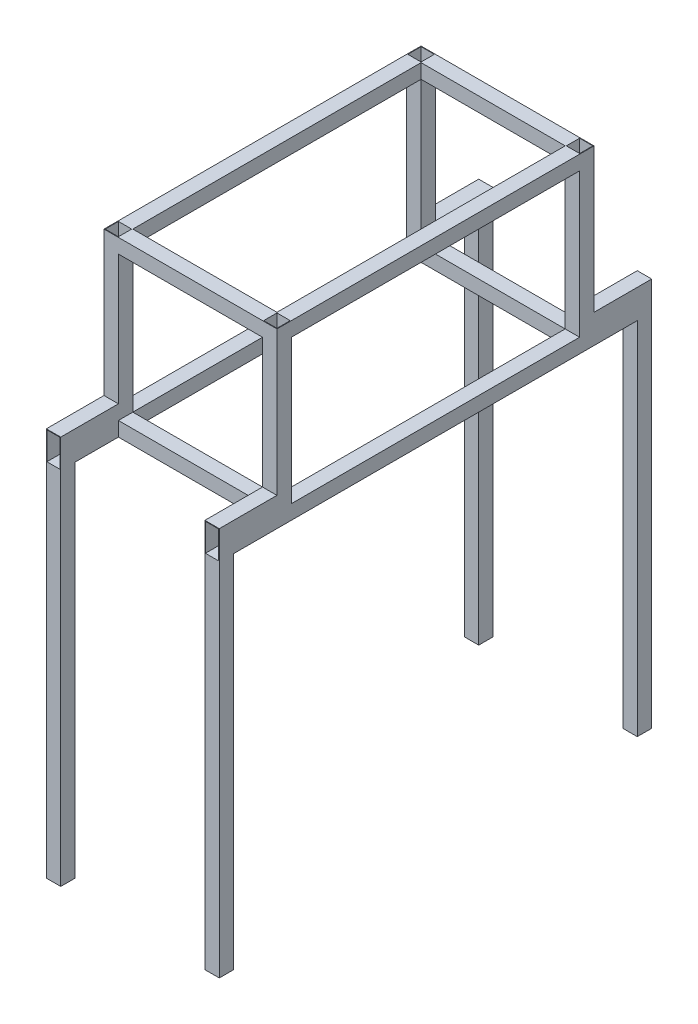
SolidWorks part; units mm, degrees
material "1023 Carbon Steel Sheet (SS)"
ref_plane "Front Plane" through (0, 0, 0) normal (0, 0, 1) x (1, 0, 0)
ref_plane "Top Plane" through (0, 0, 0) normal (0, 1, 0) x (1, 0, 0)
ref_plane "Right Plane" through (0, 0, 0) normal (1, 0, 0) x (0, 0, -1)
sketch "Sketch1" plane through (0, 0, 0) normal (0, 1, 0) x (1, 0, 0)
  line L0 (-128, 255) -> (-151.4, 255)
  line L1 (-127, 254) -> (127, 254) construction
  line L2 (-127, 254) -> (-127, -254) construction
  line L3 (-127, -254) -> (127, -254) construction
  line L4 (127, 254) -> (127, -254) construction
  line L5 (-127, 254) -> (127, -254) construction
  line L6 (-127, -254) -> (127, 254) construction
  line L7 (127, 254) -> (152.4, 254)
  line L8 (127, 254) -> (127, 279.4)
  line L9 (127, 279.4) -> (152.4, 279.4)
  line L10 (152.4, 254) -> (152.4, 279.4)
  line L11 (127, -254) -> (152.4, -254)
  line L12 (127, -254) -> (127, -279.4)
  line L13 (127, -279.4) -> (152.4, -279.4)
  line L14 (152.4, -254) -> (152.4, -279.4)
  line L15 (-127, -254) -> (-152.4, -254)
  line L16 (-127, -254) -> (-127, -279.4)
  line L17 (-127, -279.4) -> (-152.4, -279.4)
  line L18 (-152.4, -254) -> (-152.4, -279.4)
  line L19 (-127, 254) -> (-152.4, 254)
  line L20 (-127, 254) -> (-127, 279.4)
  line L21 (-127, 279.4) -> (-152.4, 279.4)
  line L22 (-152.4, 254) -> (-152.4, 279.4)
  line L23 (-151.4, 255) -> (-151.4, 278.4)
  line L24 (-128, 278.4) -> (-151.4, 278.4)
  line L25 (-128, 255) -> (-128, 278.4)
  line L26 (128, 255) -> (151.4, 255)
  line L27 (151.4, 255) -> (151.4, 278.4)
  line L28 (128, 278.4) -> (151.4, 278.4)
  line L29 (128, 255) -> (128, 278.4)
  line L30 (-128, -255) -> (-151.4, -255)
  line L31 (-151.4, -255) -> (-151.4, -278.4)
  line L32 (-128, -278.4) -> (-151.4, -278.4)
  line L33 (-128, -255) -> (-128, -278.4)
  line L34 (128, -255) -> (151.4, -255)
  line L35 (151.4, -255) -> (151.4, -278.4)
  line L36 (128, -278.4) -> (151.4, -278.4)
  line L37 (128, -255) -> (128, -278.4)
  point P0 (0, 0)
  dimension "D1" = 254
  dimension "D2" = 508
  dimension "D3" = 25.4
  dimension "D4" = 25.4
  dimension "D5" = 25.4
  dimension "D6" = 25.4
  dimension "D7" = 25.4
  dimension "D8" = 25.4
  dimension "D9" = 25.4
  dimension "D10" = 25.4
  dimension "D11" = 1
  dimension "D12" = 1
extrude "Boss-Extrude1" add sketch "Sketch1" along normal blind 304.8 contours L15 L18 L17 L16 | L11 L14 L13 L12 | L7 L10 L9 L8 | L19 L22 L21 L20 | L30 L31 L32 L33 | L34 L35 L36 L37 | L26 L27 L28 L29 | L0 L23 L24 L25
sketch "Sketch2" plane through (0, 0, -254) normal (0, 0, 1) x (1, 0, 0)
  line L0 (152.4, 304.8) -> (152.4, 0) construction
  line L1 (127, 304.8) -> (152.4, 304.8)
  line L2 (127, 304.8) -> (127, 279.4)
  line L3 (127, 279.4) -> (152.4, 279.4)
  line L4 (152.4, 304.8) -> (152.4, 279.4)
  line L5 (128, 280.4) -> (151.4, 280.4)
  line L6 (151.4, 303.8) -> (151.4, 280.4)
  line L7 (128, 303.8) -> (151.4, 303.8)
  line L8 (128, 303.8) -> (128, 280.4)
  line L9 (127, 25.4) -> (152.4, 25.4)
  line L10 (127, 25.4) -> (127, 0)
  line L11 (127, 0) -> (152.4, 0)
  line L12 (152.4, 25.4) -> (152.4, 0)
  line L13 (128, 1) -> (151.4, 1)
  line L14 (151.4, 24.4) -> (151.4, 1)
  line L15 (128, 24.4) -> (151.4, 24.4)
  line L16 (128, 24.4) -> (128, 1)
  line L17 (127, 0) -> (152.4, 0) construction
  dimension "D1" = 25.4
  dimension "D3" = 23.4
  dimension "D4" = 25.4
  dimension "D5" = 25.4
  dimension "D6" = 1
  dimension "D7" = 1
  dimension "D8" = 1
  dimension "D9" = 23.4
  dimension "D2" = 1
extrude "Boss-Extrude2" add sketch "Sketch2" along normal up to next (508 mm away)
sketch "Sketch3" plane through (127, 0, 0) normal (-1, 0, 0) x (0, 0, 1)
  line L0 (-255, 280.4) -> (-278.4, 280.4)
  line L1 (279.4, 304.8) -> (254, 304.8)
  line L2 (279.4, 304.8) -> (279.4, 279.4)
  line L3 (279.4, 279.4) -> (254, 279.4)
  line L4 (254, 304.8) -> (254, 279.4)
  line L5 (-254, 279.4) -> (-279.4, 279.4)
  line L6 (-254, 279.4) -> (-254, 304.8)
  line L7 (-254, 304.8) -> (-279.4, 304.8)
  line L8 (-279.4, 279.4) -> (-279.4, 304.8)
  line L9 (279.4, 0) -> (254, 0)
  line L10 (279.4, 0) -> (279.4, 25.4)
  line L11 (279.4, 25.4) -> (254, 25.4)
  line L12 (254, 0) -> (254, 25.4)
  line L13 (-254, 25.4) -> (-279.4, 25.4)
  line L14 (-254, 25.4) -> (-254, 0)
  line L15 (-254, 0) -> (-279.4, 0)
  line L16 (-279.4, 25.4) -> (-279.4, 0)
  line L17 (-278.4, 280.4) -> (-278.4, 303.8)
  line L18 (-255, 303.8) -> (-278.4, 303.8)
  line L19 (-255, 280.4) -> (-255, 303.8)
  line L20 (-255, 24.4) -> (-278.4, 24.4)
  line L21 (-278.4, 24.4) -> (-278.4, 1)
  line L22 (-255, 1) -> (-278.4, 1)
  line L23 (-255, 24.4) -> (-255, 1)
  line L24 (278.4, 303.8) -> (255, 303.8)
  line L25 (255, 303.8) -> (255, 280.4)
  line L26 (278.4, 280.4) -> (255, 280.4)
  line L27 (278.4, 303.8) -> (278.4, 280.4)
  line L28 (278.4, 1) -> (255, 1)
  line L29 (255, 1) -> (255, 24.4)
  line L30 (278.4, 24.4) -> (255, 24.4)
  line L31 (278.4, 1) -> (278.4, 24.4)
  dimension "D1" = 1
extrude "Boss-Extrude4" add sketch "Sketch3" along normal up to next
pattern_linear "LPattern2" count 2 spacing 279.4 along (-1, 0, 0) of "Boss-Extrude2"
sketch "Sketch4" plane through (0, 0, -279.4) normal (0, 0, -1) x (-1, 0, 0)
  line L0 (-128, 1) -> (-128, 49.8)
  line L1 (-152.4, 0) -> (-127, 0)
  line L2 (-152.4, 0) -> (-152.4, 50.8)
  line L3 (-152.4, 50.8) -> (-127, 50.8)
  line L4 (-127, 0) -> (-127, 50.8)
  line L5 (-151.4, 49.8) -> (-128, 49.8)
  line L6 (-151.4, 1) -> (-151.4, 49.8)
  line L7 (-151.4, 1) -> (-128, 1)
  line L8 (127, 50.8) -> (152.4, 50.8)
  line L9 (128, 49.8) -> (151.4, 49.8)
  line L10 (152.4, 0) -> (152.4, 50.8)
  line L11 (151.4, 1) -> (151.4, 49.8)
  line L12 (128, 1) -> (128, 49.8)
  line L13 (127, 0) -> (127, 50.8)
  line L14 (128, 1) -> (151.4, 1)
  line L15 (127, 0) -> (152.4, 0)
  dimension "D1" = 50.8
  dimension "D2" = 25.4
  dimension "D3" = 1
  dimension "D4" = 2
extrude "Boss-Extrude5" add sketch "Sketch4" along normal blind 101.6
sketch "Sketch5" plane through (0, 0, 0) normal (0, -1, 0) x (1, 0, 0)
  line L0 (-127, -381) -> (-127, -279.4) construction
  line L1 (-152.4, -381) -> (-127, -381)
  line L2 (-152.4, -381) -> (-152.4, -355.6)
  line L3 (-152.4, -355.6) -> (-127, -355.6)
  line L4 (-127, -381) -> (-127, -355.6)
  line L5 (127, -381) -> (152.4, -381)
  line L6 (127, -381) -> (127, -355.6)
  line L7 (127, -355.6) -> (152.4, -355.6)
  line L8 (152.4, -381) -> (152.4, -355.6)
  line L9 (-151.4, -380) -> (-128, -380)
  line L10 (-128, -380) -> (-128, -356.6)
  line L11 (-151.4, -356.6) -> (-128, -356.6)
  line L12 (-151.4, -380) -> (-151.4, -356.6)
  line L13 (128, -380) -> (151.4, -380)
  line L14 (151.4, -380) -> (151.4, -356.6)
  line L15 (128, -356.6) -> (151.4, -356.6)
  line L16 (128, -380) -> (128, -356.6)
  dimension "D1" = 25.4
  dimension "D3" = 1
  dimension "D2" = 2
extrude "Boss-Extrude6" add sketch "Sketch5" along normal blind 635
pattern_linear "LPattern3" count 2 spacing 660.4 along (0, 0, 1) of "Boss-Extrude5"
pattern_linear "LPattern4" count 2 spacing 736.6 along (0, 0, 1) of "Boss-Extrude6"
